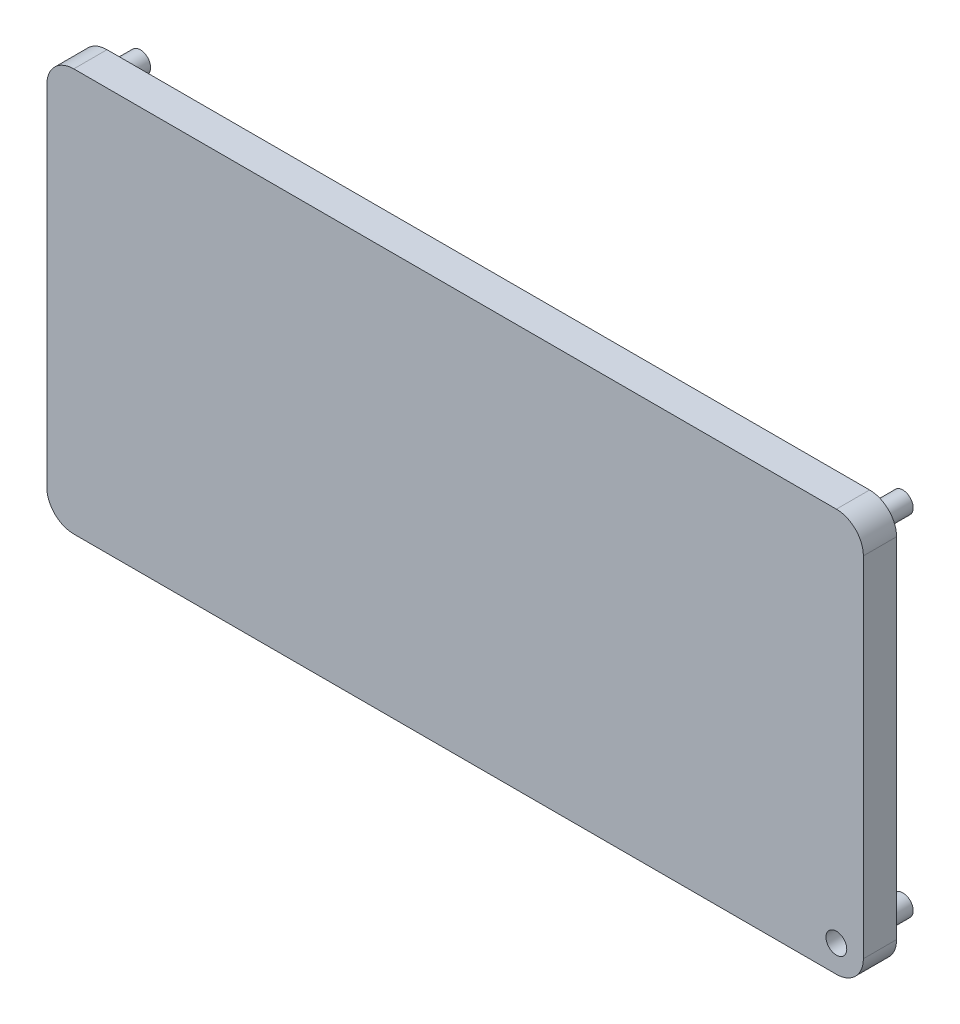
SolidWorks part; units mm, degrees
ref_plane "Front Plane" through (0, 0, 0) normal (0, 0, 1) x (1, 0, 0)
ref_plane "Top Plane" through (0, 0, 0) normal (0, 1, 0) x (1, 0, 0)
ref_plane "Right Plane" through (0, 0, 0) normal (1, 0, 0) x (0, 0, -1)
sketch "Sketch1" plane through (0, 0, 0) normal (0, 0, 1) x (1, 0, 0)
  line L0 (-63.3776, 31.75) -> (63.3776, 31.75)
  line L1 (-47.498, -14.0589) -> (47.498, -14.0589) construction
  line L2 (-47.498, -14.0589) -> (-47.498, 14.0589) construction
  line L3 (-47.498, 14.0589) -> (47.498, 14.0589) construction
  line L4 (47.498, -14.0589) -> (47.498, 14.0589) construction
  line L5 (-47.498, -14.0589) -> (47.498, 14.0589) construction
  line L6 (-47.498, 14.0589) -> (47.498, -14.0589) construction
  line L7 (-58.2976, 26.67) -> (58.2976, 26.67) construction
  line L8 (-58.2976, 26.67) -> (-58.2976, -26.67) construction
  line L9 (-58.2976, -26.67) -> (58.2976, -26.67) construction
  line L10 (58.2976, 26.67) -> (58.2976, -26.67) construction
  line L11 (-58.2976, 26.67) -> (58.2976, -26.67) construction
  line L12 (-58.2976, -26.67) -> (58.2976, 26.67) construction
  line L13 (63.3776, 31.75) -> (63.3776, -31.75)
  line L14 (-63.3776, -31.75) -> (63.3776, -31.75)
  line L15 (-63.3776, 31.75) -> (-63.3776, -31.75)
  circle A0 centre (-47.498, 14.0589) radius 1.5875 construction
  circle A1 centre (-47.498, -14.0589) radius 1.5875 construction
  circle A2 centre (47.498, 14.0589) radius 1.5875
  circle A3 centre (47.498, -14.0589) radius 1.5875
  circle A4 centre (-58.2976, 26.67) radius 1.5875
  circle A5 centre (-58.2976, -26.67) radius 1.5875
  circle A6 centre (58.2976, -26.67) radius 1.5875
  circle A7 centre (58.2976, 26.67) radius 1.5875
  circle A8 centre (-58.2976, 26.67) radius 4.1275
  circle A9 centre (58.2976, 26.67) radius 4.1275
  circle A10 centre (58.2976, -26.67) radius 4.1275
  circle A11 centre (-58.2976, -26.67) radius 4.1275
  point P0 (0, 0)
  point P10 (0, 0)
  point P31 (0, 0)
  dimension "D3" = 3.175
  dimension "D4" = 3.175
  dimension "D1" = 28.1178
  dimension "D2" = 94.996
  dimension "D7" = 53.34
  dimension "D5" = 5.08
  dimension "D6" = 2.54
extrude "Boss-Extrude1" add sketch "Sketch1" along normal blind 5.08 contours A5 | A4 | A7 | A6
sketch "Sketch3" plane through (0, 0, 5.08) normal (0, 0, 1) x (1, 0, 0)
  line L0 (-58.2976, 30.7975) -> (58.2976, 30.7975)
  line L1 (62.4251, 26.67) -> (62.4251, -26.67)
  line L2 (58.2976, -30.7975) -> (-58.2976, -30.7975)
  line L3 (-62.4251, -26.67) -> (-62.4251, 26.67)
  line L4 (63.3776, 31.75) -> (-63.3776, 31.75)
  line L5 (63.3776, -31.75) -> (63.3776, 31.75)
  line L6 (-63.3776, -31.75) -> (63.3776, -31.75)
  line L7 (-63.3776, 31.75) -> (-63.3776, -31.75)
  line L8 (63.3776, 31.75) -> (-63.3776, 31.75)
  line L9 (63.3776, -31.75) -> (63.3776, 31.75)
  line L10 (-63.3776, -31.75) -> (63.3776, -31.75)
  line L11 (-63.3776, 31.75) -> (-63.3776, -31.75)
  line L12 (-58.2976, 22.5425) -> (-58.2976, -22.5425)
  line L13 (-54.1701, -26.67) -> (54.1701, -26.67)
  line L14 (58.2976, -22.5425) -> (58.2976, 22.5425)
  line L15 (54.1701, 26.67) -> (-54.1701, 26.67)
  circle A1 centre (-58.2976, -26.67) radius 1.5875
  circle A2 centre (-58.2976, -26.67) radius 1.5875
  circle A3 centre (47.498, -14.0589) radius 1.5875
  circle A4 centre (47.498, -14.0589) radius 1.5875
  circle A5 centre (47.498, 14.0589) radius 1.5875
  circle A6 centre (47.498, 14.0589) radius 1.5875
  circle A7 centre (-58.2976, -26.67) radius 4.1275
  circle A8 centre (-58.2976, -26.67) radius 4.1275
  circle A9 centre (58.2976, -26.67) radius 4.1275
  circle A10 centre (58.2976, -26.67) radius 4.1275
  circle A11 centre (58.2976, 26.67) radius 4.1275
  circle A12 centre (58.2976, 26.67) radius 4.1275
  circle A13 centre (-58.2976, 26.67) radius 4.1275
  circle A14 centre (-58.2976, 26.67) radius 4.1275
  circle A15 centre (58.2976, 26.67) radius 1.5875
  circle A16 centre (58.2976, 26.67) radius 1.5875
  circle A17 centre (58.2976, -26.67) radius 1.5875
  circle A18 centre (58.2976, -26.67) radius 1.5875
  circle A19 centre (-58.2976, 26.67) radius 1.5875
  circle A20 centre (-58.2976, 26.67) radius 1.5875
  point P50 (0, 0)
  circle M15 centre (-58.2976, 26.67) radius 1.5875
  dimension "D1" = 0
  dimension "D2" = 0
  dimension "D3" = 0
  dimension "D4" = 0
  dimension "D5" = 0
  dimension "D6" = 0
  dimension "D7" = 0
  dimension "D8" = 0
  dimension "D9" = 0
  dimension "D10" = 0
  dimension "D11" = 0
extrude "Boss-Extrude2" add sketch "Sketch3" along normal blind 5.08 contours A14 L3 A8 L12 | A14 M15 | A14 L15 A12 L0 | A12 L14 A10 L1 | A12 A16 | A10 L13 A8 L2 | A10 A18 | A8 A2 | A2 | A16 | A14 L12 A8 L13 A10 L14 A12 L15 A6 A4 | A20
